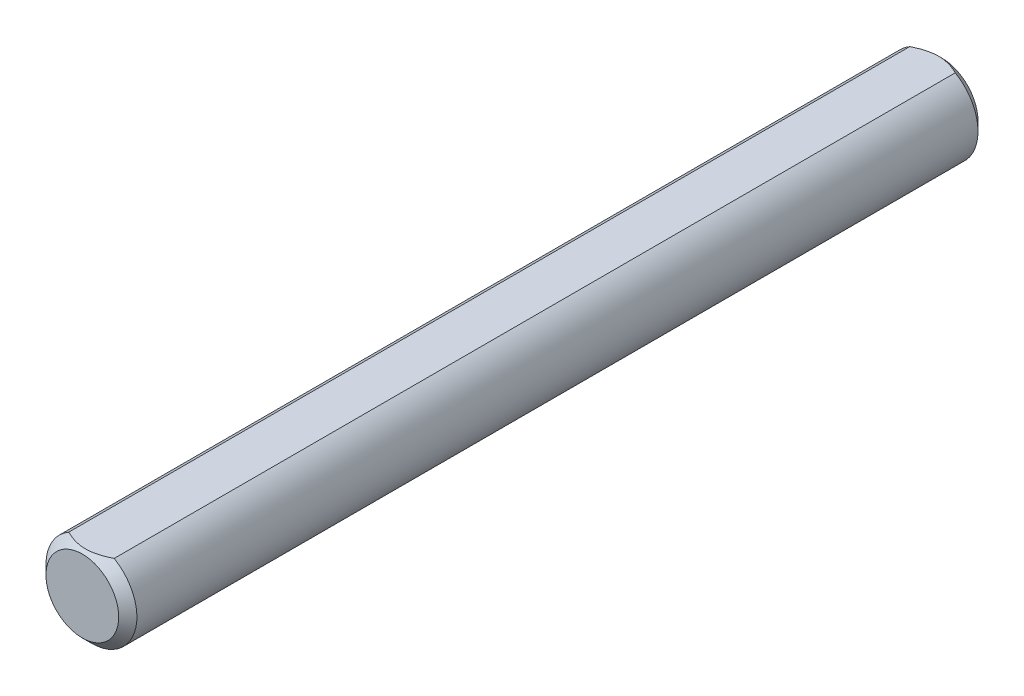
SolidWorks part; units mm, degrees
ref_plane "Front" through (0, 0, 0) normal (0, 0, 1) x (1, 0, 0)
ref_plane "Top" through (0, 0, 0) normal (0, 1, 0) x (1, 0, 0)
ref_plane "Right" through (0, 0, 0) normal (1, 0, 0) x (0, 0, -1)
sketch "Sketch1" plane through (0, 0, 0) normal (0, 0, 1) x (1, 0, 0)
  circle A0 centre (0, 0) radius 3.175
  dimension "D1" = 6.35
extrude "Extrude1" add sketch "Sketch1" along normal mid plane 60
chamfer "Chamfer1" distance 0.635 angle 45 2 edges at (3.175, 0, -30) (3.175, 0, 30)
sketch "Sketch13" plane through (0, 0, 0) normal (0, 0, 1) x (1, 0, 0)
  line L3 (-1.5875, 2.7496) -> (1.5875, 2.7496)
  circle A0 centre (0, 0) radius 3.175 construction
  arc A1 (1.5875, 2.7496) -> (-1.5875, 2.7496) centre (0, 0) ccw
  dimension "D1" = 3.175
extrude "Extrude7" cut sketch "Sketch13" against normal through all and the other way through all
equation "\"D1@Chamfer1\" = \"D1@Sketch1\" * .1"
equation "\"D1@Sketch13\" = \"D1@Sketch1\" * .5"
